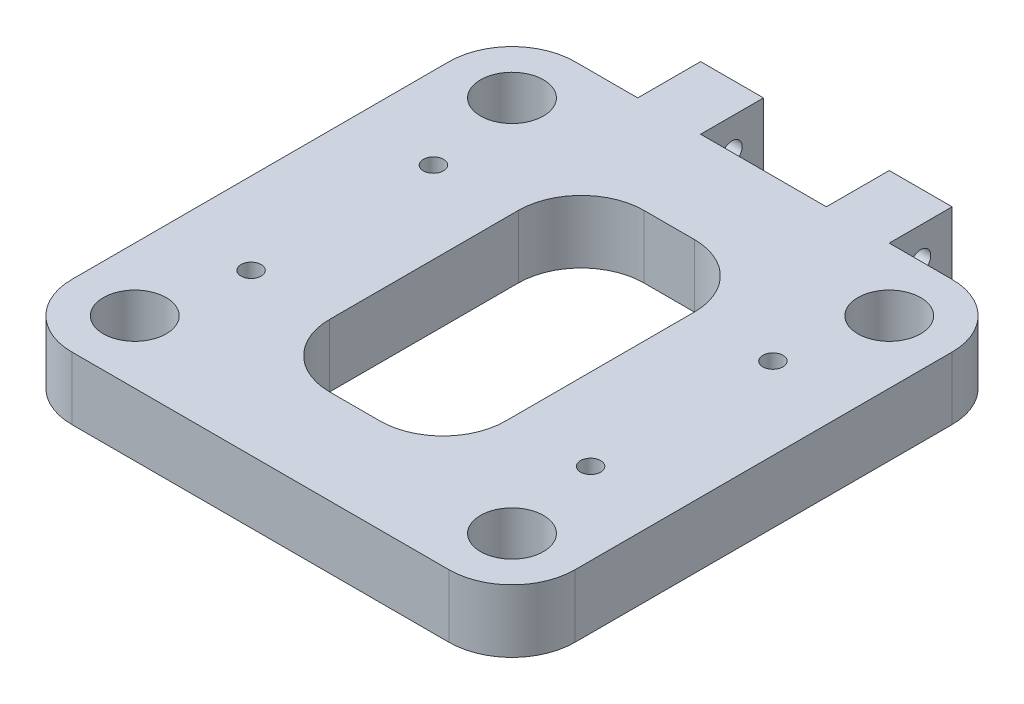
SolidWorks part; units mm, degrees
ref_plane "正面" through (0, 0, 0) normal (0, 0, 1) x (1, 0, 0)
ref_plane "平面" through (0, 0, 0) normal (0, 1, 0) x (1, 0, 0)
ref_plane "右側面" through (0, 0, 0) normal (1, 0, 0) x (0, 0, -1)
sketch "ｽｹｯﾁ1" plane through (0, 0, 0) normal (0, 1, 0) x (1, 0, 0)
  line L1 (-40, -40) -> (40, -40)
  line L2 (-40, -40) -> (-40, 40)
  line L3 (-40, 40) -> (40, 40)
  line L4 (40, -40) -> (40, 40)
  line L5 (-40, -40) -> (40, 40) construction
  line L6 (-40, 40) -> (40, -40) construction
  point P0 (0, 0)
  dimension "D1" = 80
extrude "ﾎﾞｽ - 押し出し1" add sketch "ｽｹｯﾁ1" along normal blind 10
fillet "ﾌｨﾚｯﾄ1" radius 10 4 edges at (-40, 5, -40) (40, 5, -40) (40, 5, 40) (-40, 5, 40)
sketch "ｽｹｯﾁ3" plane through (0, 10, 0) normal (0, 1, 0) x (1, 0, 0)
  line L0 (-40, 30) -> (-40, -30) construction
  line L1 (-4, -25) -> (4, -25)
  line L2 (-14, -15) -> (-14, 15)
  line L3 (-4, 25) -> (4, 25)
  line L4 (14, -15) -> (14, 15)
  line L5 (-14, -25) -> (14, 25) construction
  line L6 (-14, 25) -> (14, -25) construction
  arc A0 (4, -25) -> (14, -15) centre (4, -15) ccw
  arc A1 (-4, -25) -> (-14, -15) centre (-4, -15) cw
  arc A2 (4, 25) -> (14, 15) centre (4, 15) cw
  arc A3 (-14, 15) -> (-4, 25) centre (-4, 15) cw
  point P0 (0, 0)
  dimension "D1" = 26
  dimension "D3" = 10
  dimension "D2" = 50
extrude "ｶｯﾄ - 押し出し2" cut sketch "ｽｹｯﾁ3" against normal through all
sketch "ｽｹｯﾁ4" plane through (0, 10, 0) normal (0, 1, 0) x (1, 0, 0)
  circle A0 centre (-30, 30) radius 5
  circle A1 centre (30, 30) radius 5
  circle A2 centre (-30, -30) radius 5
  circle A3 centre (30, -30) radius 5
  arc A4 (-30, 40) -> (-40, 30) centre (-30, 30) ccw construction
  arc A5 (-40, -30) -> (-30, -40) centre (-30, -30) ccw construction
  arc A6 (30, -40) -> (40, -30) centre (30, -30) ccw construction
  arc A7 (40, 30) -> (30, 40) centre (30, 30) ccw construction
  dimension "D1" = 10
extrude "ｶｯﾄ - 押し出し5" cut sketch "ｽｹｯﾁ4" against normal through all
sketch "ｽｹｯﾁ5" plane through (0, 0, 0) normal (0, -1, 0) x (1, 0, 0)
  line L0 (40, 30) -> (40, -30) construction
  line L1 (-40, -30) -> (-40, 30) construction
  circle A0 centre (27, 14.5) radius 1.6
  circle A1 centre (-27, 14.5) radius 1.6
  circle A2 centre (-27, -14.5) radius 1.6
  circle A3 centre (27, -14.5) radius 1.6
  point P12 (40, 0)
  point P15 (-40, 0)
  dimension "D3" = 3.2
  dimension "D4" = 13
  dimension "D5" = 13
  dimension "D1" = 14.5
  dimension "D2" = 14.5
  dimension "D6" = 13
  dimension "D7" = 13
  dimension "D8" = 14.5
  dimension "D9" = 14.5
extrude "ｶｯﾄ - 押し出し3" cut sketch "ｽｹｯﾁ5" against normal through all
sketch "ｽｹｯﾁ6" plane through (0, 0, -40) normal (0, 0, -1) x (-1, 0, 0)
  line L0 (-30, 10) -> (30, 10) construction
  line L1 (-20, 10) -> (-10, 10)
  line L2 (-20, 10) -> (-20, 0)
  line L3 (-20, 0) -> (-10, 0)
  line L4 (-10, 10) -> (-10, 0)
  line L5 (-20, 10) -> (-10, 0) construction
  line L6 (-20, 0) -> (-10, 10) construction
  line L7 (-30, 0) -> (30, 0) construction
  line L9 (10, 10) -> (20, 10)
  line L10 (10, 10) -> (10, 0)
  line L11 (10, 0) -> (20, 0)
  line L12 (20, 10) -> (20, 0)
  line L13 (10, 10) -> (20, 0) construction
  line L14 (10, 0) -> (20, 10) construction
  point P4 (-15, 5)
  point P13 (15, 5)
  dimension "D1" = 15
  dimension "D2" = 15
extrude "ﾎﾞｽ - 押し出し3" add sketch "ｽｹｯﾁ6" along normal blind 10
sketch "ｽｹｯﾁ7" plane through (0, 0, 0) normal (1, 0, 0) x (0, 0, -1)
  line L0 (50, 10) -> (40, 10) construction
  line L1 (50, 10) -> (50, 0) construction
  circle A0 centre (45, 5) radius 1.6
  point P4 (45, 10)
  point P7 (50, 5)
  dimension "D1" = 3.2
extrude "ｶｯﾄ - 押し出し4" cut sketch "ｽｹｯﾁ7" against normal through all both and the other way through all
